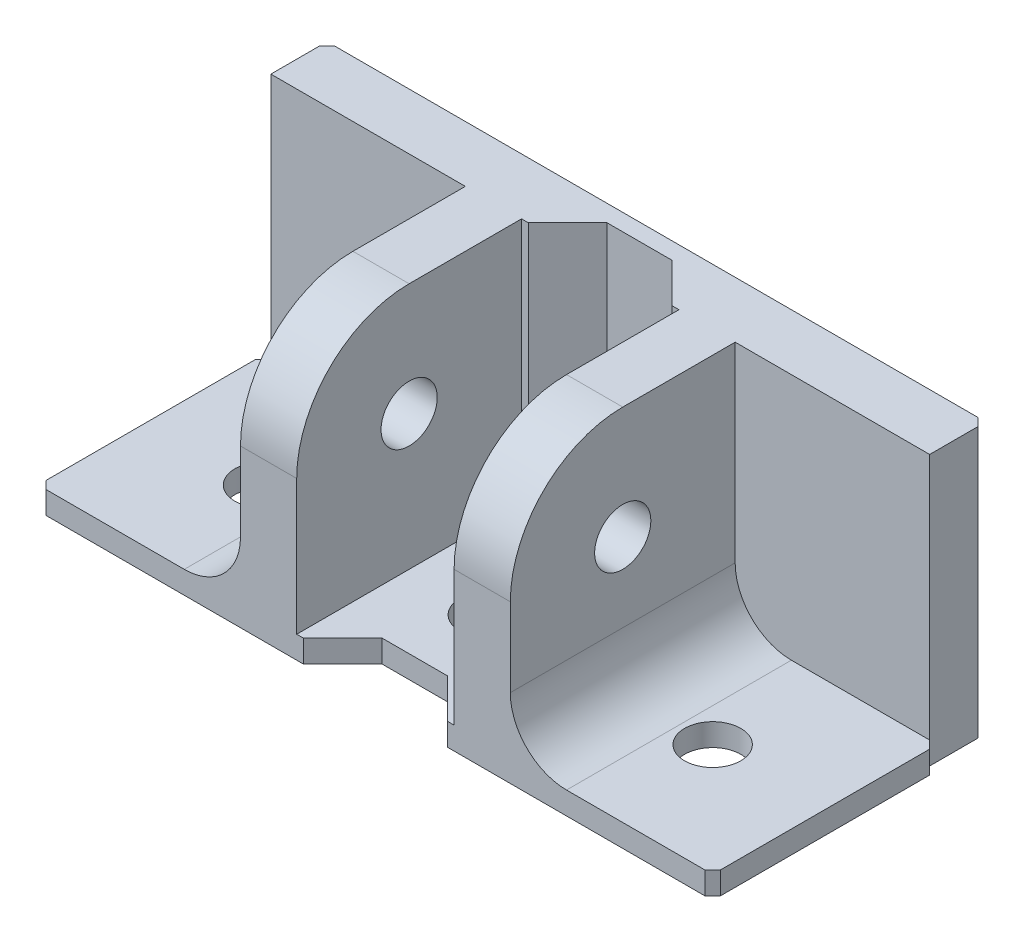
SolidWorks part; units mm, degrees
ref_plane "Front Plane" through (0, 0, 0) normal (0, 0, 1) x (1, 0, 0)
ref_plane "Top Plane" through (0, 0, 0) normal (0, 1, 0) x (1, 0, 0)
ref_plane "Right Plane" through (0, 0, 0) normal (1, 0, 0) x (0, 0, -1)
sketch "Sketch1" plane through (0, 0, 0) normal (0, 1, 0) x (1, 0, 0)
  line L0 (0, 0) -> (60, 0)
  line L1 (-36.8738, 0) -> (36.8738, 0) construction
  line L2 (60, 0) -> (60, 20)
  line L3 (60, 20) -> (0, 20)
  line L4 (0, -13.1266) -> (0, 13.1266) construction
  line L5 (0, 20) -> (0, 0)
  circle A0 centre (10, 10) radius 2.5
  circle A1 centre (30, 10) radius 2.5
  circle A2 centre (50, 10) radius 2.5
  dimension "D3" = 5
  dimension "D4" = 5
  dimension "D5" = 5
  dimension "D7" = 10
  dimension "D8" = 20
  dimension "D9" = 10
  dimension "D11" = 10
  dimension "D1" = 60
  dimension "D2" = 20
  dimension "D6" = 10
  dimension "D10" = 20
extrude "Boss-Extrude1" add sketch "Sketch1" along normal blind 2
fillet "Fillet1" radius 0.7 4 edges at (0, 1, -20) (0, 1, 0) (60, 1, 0) (60, 1, -20) profile chamfer
sketch "Sketch2" plane through (0, 2, 0) normal (0, 1, 0) x (1, 0, 0)
  line L0 (30, 10) -> (30, 20)
  line L1 (59.3, 20) -> (0.7, 20) construction
  line L2 (30, 10) -> (30, 0)
  line L3 (-2.2, 0) -> (2.2, 0) construction
  line L4 (30, 20) -> (32.9, 20)
  line L5 (30, 20) -> (27.1, 20)
  line L7 (27.1, 16.5) -> (32.9, 16.5)
  line L9 (27.1, 16.5) -> (23.6, 20)
  line L10 (32.9, 16.5) -> (36.4, 20)
  line L11 (32.9, 20) -> (36.4, 20)
  line L12 (27.1, 20) -> (23.6, 20)
  line L13 (30, 0) -> (32.9, 0)
  line L14 (30, 0) -> (27.1, 0)
  line L16 (32.9, 3.5) -> (27.1, 3.5)
  line L18 (32.9, 3.5) -> (36.4, 0)
  line L19 (27.1, 3.5) -> (23.6, 0)
  point P10 (31.45, 20)
  line M2 (59.3, 20) -> (0.7, 20)
  line M6 (0.7, 0) -> (59.3, 0)
  dimension "D1" = 2.9
  dimension "D2" = 2.9
  dimension "D3" = 3.5
  dimension "D4" = 3.5
  dimension "D5" = 4.9497
  dimension "D6" = 4.9497
  dimension "D7" = 2.9
  dimension "D8" = 2.9
  dimension "D9" = 3.5
  dimension "D10" = 3.5
  dimension "D11" = 4.9497
  dimension "D12" = 225
  dimension "D13" = 135
extrude "Cut-Extrude2" cut sketch "Sketch2" against normal blind 2 contours L7 L10 L0 M2 | L9 L7 L0 M2 | L16 L19 L2 M6 | L18 L16 L2 M6
sketch "Sketch3" plane through (0, 2, 0) normal (0, 1, 0) x (1, 0, 0)
  line L0 (30, 10) -> (23, 10)
  line L1 (30, 10) -> (37, 10)
  line L2 (37, 10) -> (37, 20)
  line L3 (59.3, 20) -> (36.4, 20) construction
  line L4 (37, 10) -> (37, 0)
  line L5 (-1.1, 0) -> (1.1, 0) construction
  line L6 (37, 0) -> (42, 0)
  line L7 (42, 0) -> (42, 20)
  line L8 (42, 20) -> (37, 20)
  line L9 (23, 10) -> (23, 20)
  line L10 (23.6, 20) -> (0.7, 20) construction
  line L11 (23, 20) -> (18, 20)
  line L12 (18, 20) -> (18, 0)
  line L13 (23, 10) -> (23, 0)
  line L14 (23, 0) -> (18, 0)
  line M6 (23.6, 20) -> (0.7, 20)
  line M10 (0.7, 0) -> (23.6, 0)
  line M14 (36.4, 0) -> (59.3, 0)
  line M18 (59.3, 20) -> (36.4, 20)
  dimension "D1" = 7
  dimension "D2" = 7
  dimension "D3" = 20
  dimension "D4" = 10
extrude "Boss-Extrude3" add sketch "Sketch3" along normal blind 22 contours L13 L9 L12 M6 M10 | L7 L2 L4 M14 M18
sketch "Sketch4" plane through (0, 0, 0) normal (0, 1, 0) x (1, 0, 0)
  line L0 (0.7, 20) -> (0.7, 25)
  line L1 (0.7, 25) -> (59.3, 25)
  line L2 (59.3, 25) -> (59.3, 20)
  line L3 (0.7, 20) -> (23.6, 20)
  line L4 (23.6, 20) -> (59.3, 20)
  dimension "D1" = 5
extrude "Boss-Extrude4" add sketch "Sketch4" along normal blind 24
sketch "Sketch5" plane through (0, 24, 0) normal (0, 1, 0) x (1, 0, 0)
  line L0 (23.6, 20) -> (27.1002, 23.5002)
  line L1 (23, 20) -> (37, 20) construction
  line L2 (32.9002, 23.5002) -> (36.4, 20)
  line L3 (27.1002, 23.5002) -> (32.9002, 23.5002)
  line L4 (23.6, 20) -> (36.4, 20)
  dimension "D1" = 45
  dimension "D2" = 4.95
  dimension "D3" = 5.8
extrude "Cut-Extrude3" cut sketch "Sketch5" against normal blind 24
sketch "Sketch6" plane through (42, 0, 0) normal (1, 0, 0) x (0, 0, -1)
  line L0 (0.7, 2) -> (19.3, 2) construction
  line L1 (20, 24) -> (20, 2) construction
  circle A0 centre (10, 14) radius 2.5
  point P4 (0, 0)
  point P6 (0, 0)
  dimension "D1" = 12
  dimension "D2" = 10
extrude "Cut-Extrude4" cut sketch "Sketch6" against normal through all
fillet "Fillet2" radius 10 2 edges at (20.5, 24, 0) (39.5, 24, 0)
fillet "Fillet4" radius 5 2 edges at (18, 2, -10) (42, 2, -10)
chamfer "Chamfer1" distance 0.7 angle 45 2 edges at (0.7, 12, -25) (59.3, 12, -25)
